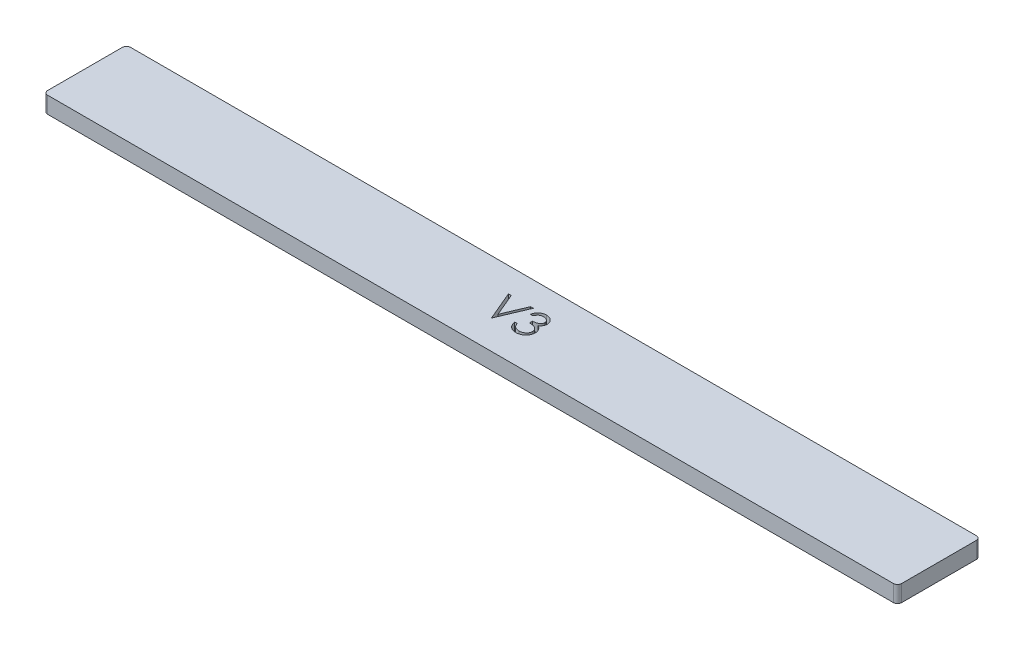
SolidWorks part; units mm, degrees
ref_plane "Front Plane" through (0, 0, 0) normal (0, 0, 1) x (1, 0, 0)
ref_plane "Top Plane" through (0, 0, 0) normal (0, 1, 0) x (1, 0, 0)
ref_plane "Right Plane" through (0, 0, 0) normal (1, 0, 0) x (0, 0, -1)
sketch "Sketch1" plane through (0, 0, 0) normal (0, 1, 0) x (1, 0, 0)
  line L1 (-49.5, 3) -> (49.5, 3)
  line L2 (-49.5, 3) -> (-49.5, -3)
  line L3 (-49.5, -3) -> (49.5, -3)
  line L4 (49.5, 3) -> (49.5, -3)
  line L5 (-49.5, 3) -> (49.5, -3) construction
  line L6 (-49.5, -3) -> (49.5, 3) construction
  point P0 (0, 0)
  dimension "D1" = 99
  dimension "D2" = 6
extrude "Boss-Extrude1" add sketch "Sketch1" along normal blind 2
sketch "Sketch2" plane through (0, 2, 0) normal (0, 1, 0) x (1, 0, 0)
  line L0 (50.5, -4) -> (50.5, 4)
  line L1 (50.5, 4) -> (-50.5, 4)
  line L2 (-50.5, 4) -> (-50.5, -4)
  line L3 (-50.5, -4) -> (50.5, -4)
  line L4 (49.5, -3) -> (49.5, 3)
  line L5 (49.5, 3) -> (-49.5, 3)
  line L6 (-49.5, 3) -> (-49.5, -3)
  line L7 (-49.5, -3) -> (49.5, -3)
  line L8 (49.5, -3) -> (49.5, 3) construction
  line L9 (49.5, 3) -> (-49.5, 3) construction
  line L10 (-49.5, 3) -> (-49.5, -3) construction
  line L11 (-49.5, -3) -> (49.5, -3) construction
  dimension "D1" = 0
  dimension "D2" = 1
extrude "Boss-Extrude3" add sketch "Sketch2" along normal blind 2 separate body
draft "Draft1" type of draft neutral plane draft angle 10 faces to draft 4 face at (49.5, 1, 0) face at (0, 1, 3) face at (-49.5, 1, 0) face at (0, 1, -3) neutral plane through (0, 0, 0) neutral plane normal (0, -1, 0) parameters "D1"=10
sketch "Sketch3" plane through (0, 4, 0) normal (0, 1, 0) x (1, 0, 0)
  line L0 (-51.5, -5) -> (51.5, -5)
  line L1 (51.5, -5) -> (51.5, 5)
  line L2 (51.5, 5) -> (-51.5, 5)
  line L3 (-51.5, 5) -> (-51.5, -5)
  line L4 (-50.5, -4) -> (50.5, -4)
  line L5 (50.5, -4) -> (50.5, 4)
  line L6 (50.5, 4) -> (-50.5, 4)
  line L7 (-50.5, 4) -> (-50.5, -4)
  line L8 (-50.5, -4) -> (50.5, -4)
  line L9 (50.5, -4) -> (50.5, 4)
  line L10 (50.5, 4) -> (-50.5, 4)
  line L11 (-50.5, 4) -> (-50.5, -4)
  dimension "D1" = 0
  dimension "D2" = 1
extrude "Boss-Extrude4" add sketch "Sketch3" against normal blind 2
fillet "Fillet1" radius 0.5 4 edges at (-51.5, 3, -5) (51.5, 3, -5) (51.5, 3, 5) (-51.5, 3, 5)
sketch "Sketch4" plane through (0, 4, 0) normal (0, 1, 0) x (1, 0, 0)
  text T1 "V3\r\n"
extrude "Cut-Extrude1" cut sketch "Sketch4" against normal blind 1
sketch "Sketch5" plane through (0, 2, 0) normal (0, -1, 0) x (1, 0, 0)
  line L4 (-51.5, 4.5) -> (-51.5, -4.5)
  line L5 (-51, -5) -> (51, -5)
  line L6 (51.5, -4.5) -> (51.5, 4.5)
  line L7 (51, 5) -> (-51, 5)
  line L8 (-51.5, 4.5) -> (-51.5, -4.5)
  line L9 (-51, -5) -> (51, -5)
  line L10 (51.5, -4.5) -> (51.5, 4.5)
  line L11 (51, 5) -> (-51, 5)
  arc A4 (-51.5, -4.5) -> (-51, -5) centre (-51, -4.5) ccw
  arc A5 (51, -5) -> (51.5, -4.5) centre (51, -4.5) ccw
  arc A6 (51.5, 4.5) -> (51, 5) centre (51, 4.5) ccw
  arc A7 (-51, 5) -> (-51.5, 4.5) centre (-51, 4.5) ccw
  arc A8 (-51.5, -4.5) -> (-51, -5) centre (-51, -4.5) ccw
  arc A9 (51, -5) -> (51.5, -4.5) centre (51, -4.5) ccw
  arc A10 (51.5, 4.5) -> (51, 5) centre (51, 4.5) ccw
  arc A11 (-51, 5) -> (-51.5, 4.5) centre (-51, 4.5) ccw
  dimension "D1" = 0
extrude "Cut-Extrude2" cut sketch "Sketch5" along normal blind 10
